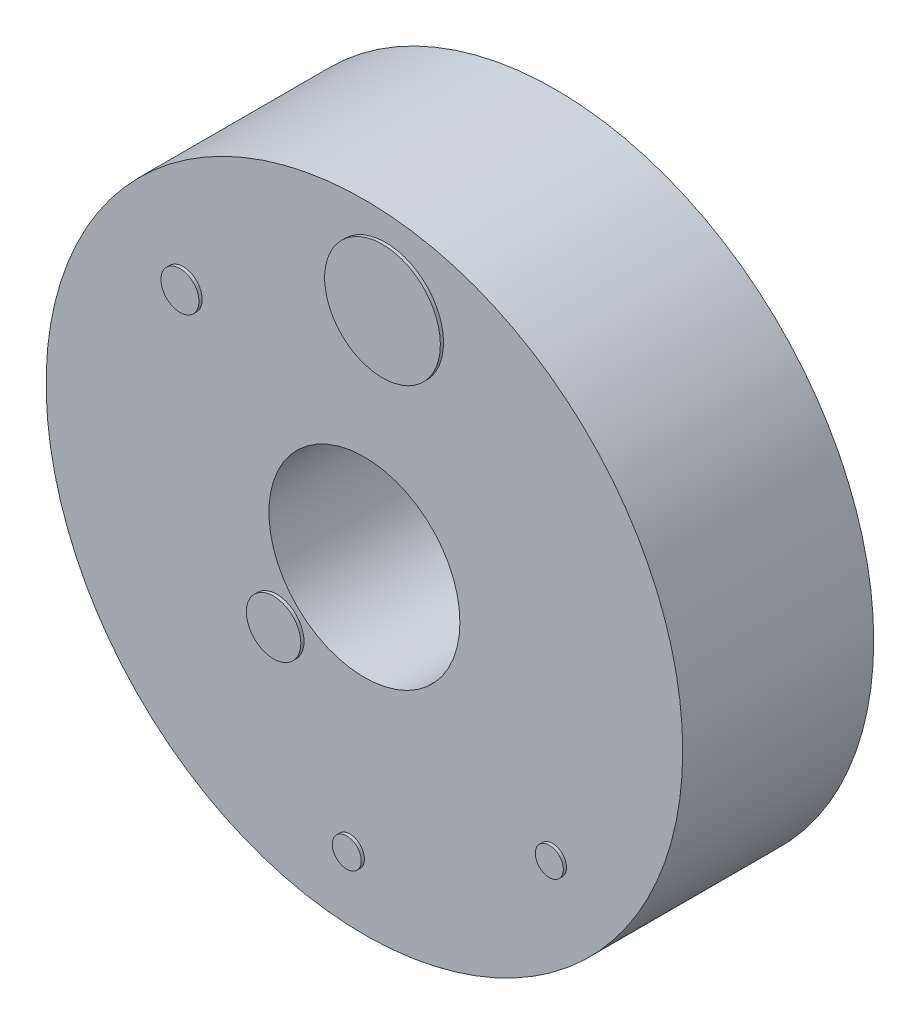
SolidWorks part; units mm, degrees
ref_plane "Plano frontal" through (0, 0, 0) normal (0, 0, 1) x (1, 0, 0)
ref_plane "Plano superior" through (0, 0, 0) normal (0, 1, 0) x (1, 0, 0)
ref_plane "Plano direito" through (0, 0, 0) normal (1, 0, 0) x (0, 0, -1)
sketch "Esboço1" plane through (0, 0, 0) normal (0, 0, 1) x (1, 0, 0)
  circle A0 centre (0, 0) radius 10
  circle A1 centre (0, 0) radius 3
  dimension "D1" = 6
  dimension "D2" = 20
extrude "Ressalto-extrusão1" add sketch "Esboço1" along normal blind 6
sketch "Esboço2" plane through (0, 0, 6) normal (0, 0, 1) x (1, 0, 0)
  circle A0 centre (-5.6942, 4.7318) radius 0.5978
  circle A1 centre (0.6683, 7.3517) radius 1.8179
  circle A2 centre (5.9081, -4.9991) radius 0.4409
  circle A3 centre (-2.7535, -2.9674) radius 0.8555
  circle A5 centre (-0.4545, -7.9398) radius 0.4545
extrude "Ressalto-extrusão2" add sketch "Esboço2" along normal blind 0.1 contours A1 | A3 | A2 | A5 | A0
